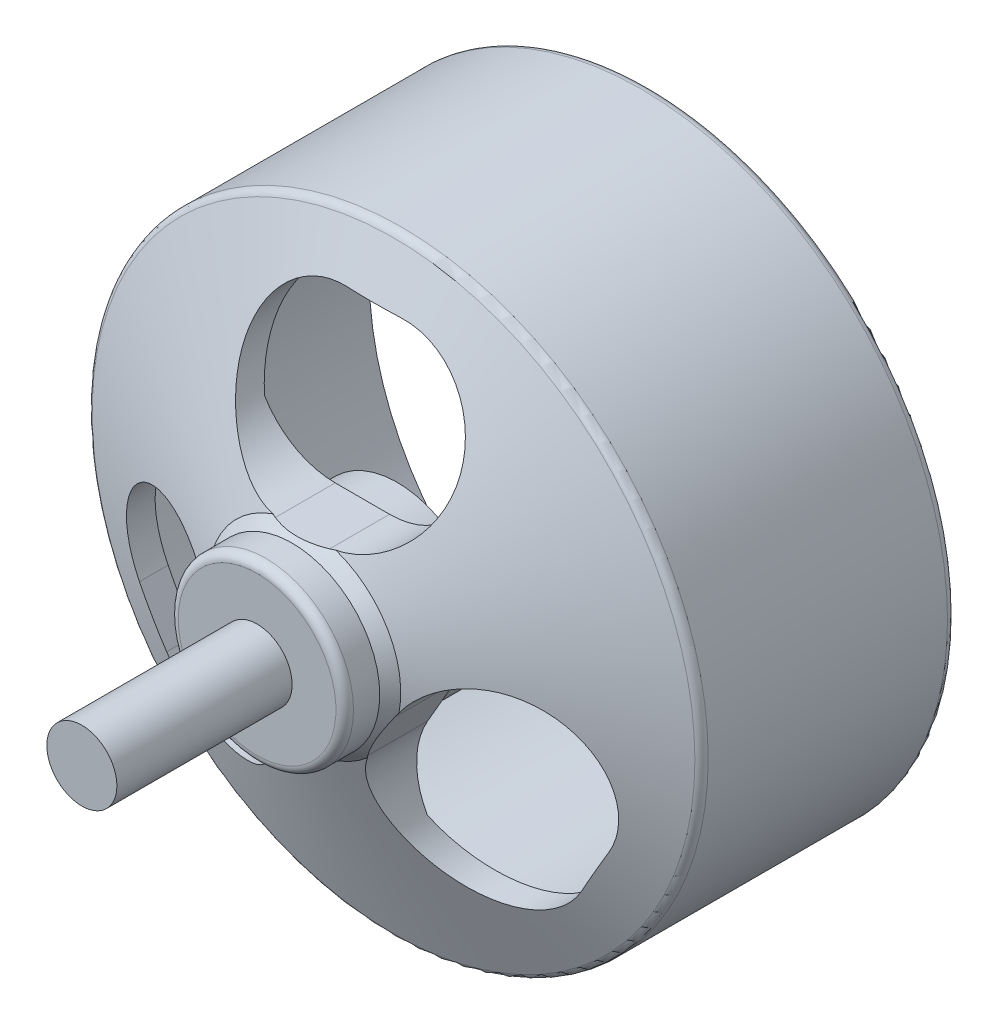
SolidWorks part; units mm, degrees
ref_plane "Спереди" through (0, 0, 0) normal (0, 0, 1) x (1, 0, 0)
ref_plane "Сверху" through (0, 0, 0) normal (0, 1, 0) x (1, 0, 0)
ref_plane "Справа" through (0, 0, 0) normal (1, 0, 0) x (0, 0, -1)
sketch "Эскиз1" plane through (0, 0, 0) normal (1, 0, 0) x (0, 0, -1)
  line L1 (-9, 0) -> (-9, 2)
  line L2 (-9, 2) -> (1, 2)
  line L3 (1, 2) -> (1, 5)
  line L4 (1, 5) -> (3, 5)
  line L5 (3, 5) -> (3.7, 5.5)
  line L6 (3.7, 5.5) -> (8.9165, 17.5)
  line L7 (8.9165, 17.5) -> (23.4, 17.5)
  line L8 (23.4, 17.5) -> (23.4, 16)
  line L9 (23.4, 16) -> (9.9, 16)
  line L10 (9.9, 16) -> (7.0092, 9.35)
  line L11 (7.0092, 9.35) -> (7.0092, 5)
  line L12 (7.0092, 5) -> (9, 5)
  line L13 (9, 5) -> (9, 0)
  line L15 (-9, 0) -> (9, 0)
  line L16 (9, 0) -> (20.1942, 0) construction
  dimension "D1" = 4
  dimension "D2" = 10
  dimension "D3" = 8
  dimension "D4" = 10
  dimension "D5" = 18.7
  dimension "D6" = 1.5
  dimension "D7" = 0.7
  dimension "D8" = 13.5
  dimension "D9" = 22.4
  dimension "D10" = 0.5
  dimension "D11" = 2
  dimension "D12" = 32
  dimension "D13" = 35
revolve "Повернуть1" add sketch "Эскиз1" angle 360 about L16
sketch "Эскиз2" plane through (0, 0, -1) normal (0, 0, 1) x (1, 0, 0)
  line L0 (1.55, 14.5641) -> (-1.55, 14.5641)
  line L1 (1.55, 5.1941) -> (-1.55, 5.1941)
  line L2 (1.55, 9.8791) -> (-1.55, 9.8791) construction
  line L3 (0, 9.8791) -> (0, 0) construction
  circle A0 centre (0, 0) radius 10 construction
  arc A1 (-1.55, 14.5641) -> (-1.55, 5.1941) centre (-1.55, 9.8791) ccw
  arc A2 (1.55, 5.1941) -> (1.55, 14.5641) centre (1.55, 9.8791) ccw
  dimension "D2" = 20
  dimension "D3" = 9.37
  dimension "D1" = 3.1
extrude "Вырез-Вытянуть1" cut sketch "Эскиз2" against normal blind 10
pattern_circular "Круговой массив1" count 3 over 360 about axis through (0, 0, 0) along (0, 0, 1) of "Вырез-Вытянуть1"
fillet "Скругление1" radius 0.5 3 edges at (17.5, 0, -23.4) (17.5, 0, -8.9165) (5, 0, -1)
scale "Масштаб1" scale about centroid uniform scaling yes scale factor 0.5
